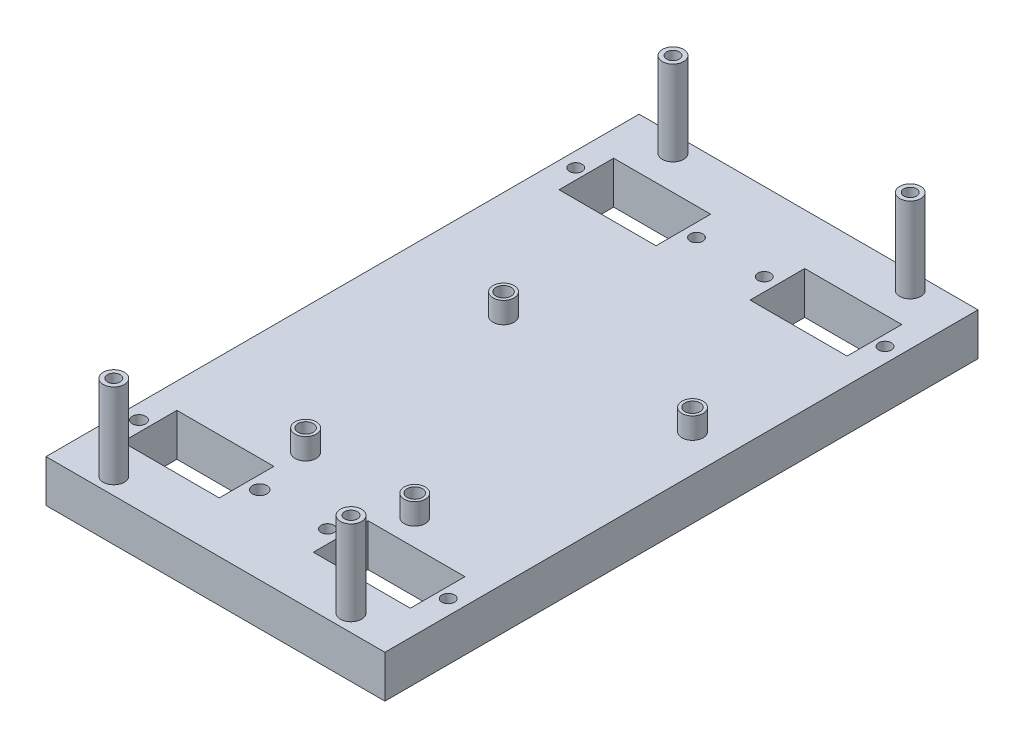
SolidWorks part; units mm, degrees
material "ABS PC"
ref_plane "Front Plane" through (0, 0, 0) normal (0, 0, 1) x (1, 0, 0)
ref_plane "Top Plane" through (0, 0, 0) normal (0, 1, 0) x (1, 0, 0)
ref_plane "Right Plane" through (0, 0, 0) normal (1, 0, 0) x (0, 0, -1)
sketch "Sketch1" plane through (0, 0, 0) normal (0, 1, 0) x (1, 0, 0)
  line L1 (0, 0) -> (-80, 0)
  line L2 (0, 0) -> (0, 140)
  line L3 (0, 140) -> (-80, 140)
  line L4 (-80, 0) -> (-80, 140)
  dimension "D1" = 140
  dimension "D2" = 80
extrude "Boss-Extrude1" add sketch "Sketch1" along normal blind 10
sketch "Sketch4" plane through (0, 10, 0) normal (0, 1, 0) x (1, 0, 0)
  line L0 (0, 140) -> (-80, 140) construction
  line L1 (-6, 128) -> (-28.9, 128)
  line L2 (-6, 128) -> (-6, 115.1)
  line L3 (-6, 115.1) -> (-28.9, 115.1)
  line L4 (-28.9, 128) -> (-28.9, 115.1)
  line L5 (0, 0) -> (0, 140) construction
  dimension "D1" = 12
  dimension "D2" = 12.9
  dimension "D3" = 22.9
  dimension "D4" = 6
extrude "Cut-Extrude2" cut sketch "Sketch4" against normal through all
sketch "Sketch6" plane through (0, 10, 0) normal (0, 1, 0) x (1, 0, 0)
  line L0 (-6, 115.1) -> (-6, 128) construction
  line L1 (0, 140) -> (-80, 140) construction
  circle A0 centre (-3.5, 121.55) radius 1.5
  circle A1 centre (-32, 121.55) radius 1.5
  dimension "D2" = 3
  dimension "D5" = 3
  dimension "D1" = 28.5
  dimension "D3" = 18.45
  dimension "D4" = 18.45
  dimension "D6" = 2.5
extrude "Cut-Extrude4" cut sketch "Sketch6" against normal through all
ref_plane "Plane18" through (0, 0, -70) normal (0, 0, 1) x (1, 0, 0)
mirror "Mirror4" about plane through (0, 0, -70) normal (0, 0, 1) of "Cut-Extrude2", "Cut-Extrude4"
ref_plane "Plane19" through (-40, 0, 0) normal (-1, 0, 0) x (0, 0, 1)
mirror "Mirror15" about plane through (-40, 0, 0) normal (-1, 0, 0) of "Cut-Extrude4", "Cut-Extrude2"
sketch "Sketch9" plane through (0, 10, 0) normal (0, 1, 0) x (1, 0, 0)
  line L1 (-51.1, 24.9) -> (-74, 24.9)
  line L2 (-51.1, 24.9) -> (-51.1, 12)
  line L3 (-51.1, 12) -> (-74, 12)
  line L4 (-74, 24.9) -> (-74, 12)
  line L6 (-80, 140) -> (-80, 0) construction
  line L7 (-80, 0) -> (0, 0) construction
  dimension "D1" = 12.9
  dimension "D2" = 22.9
  dimension "D3" = 6
  dimension "D4" = 12
extrude "Cut-Extrude5" cut sketch "Sketch9" against normal through all
sketch "Sketch13" plane through (0, 10, 0) normal (0, 1, 0) x (1, 0, 0)
  line L0 (0, 140) -> (-80, 140) construction
  line L1 (-80, 140) -> (-80, 0) construction
  circle A0 centre (-68, 136) radius 2.5
  dimension "D3" = 5
  dimension "D1" = 4
  dimension "D2" = 12
extrude "Boss-Extrude2" add sketch "Sketch13" along normal blind 20
sketch "Sketch14" plane through (0, 30, 0) normal (0, 1, 0) x (1, 0, 0)
  circle A0 centre (-68, 136) radius 1.5
  dimension "D1" = 3
extrude "Cut-Extrude8" cut sketch "Sketch14" against normal blind 5
sketch "Sketch15" plane through (0, 10, 0) normal (0, 1, 0) x (1, 0, 0)
  line L0 (0, 140) -> (-80, 140) construction
  line L1 (0, 0) -> (0, 140) construction
  circle A0 centre (-12, 136) radius 2.5
  dimension "D3" = 5
  dimension "D1" = 4
  dimension "D2" = 12
extrude "Boss-Extrude3" add sketch "Sketch15" along normal blind 20
sketch "Sketch16" plane through (0, 30, 0) normal (0, 1, 0) x (1, 0, 0)
  circle A0 centre (-12, 136) radius 1.5
  dimension "D1" = 3
extrude "Cut-Extrude9" cut sketch "Sketch16" against normal blind 5
mirror "Mirror22" about plane through (0, 0, -70) normal (0, 0, 1) of "Cut-Extrude9", "Boss-Extrude3", "Cut-Extrude8", "Boss-Extrude2"
sketch "Sketch17" plane through (0, 10, 0) normal (0, 1, 0) x (1, 0, 0)
  line L2 (-74, 24.9) -> (-74, 12) construction
  line L3 (-80, 0) -> (0, 0) construction
  circle A0 centre (-76.5, 18.45) radius 1.5673
  circle A1 centre (-48, 18.45) radius 1.7104
  dimension "D2" = 2.5
  dimension "D3" = 18.45
  dimension "D4" = 18.45
  dimension "D1" = 28.5
extrude "Cut-Extrude10" cut sketch "Sketch17" against normal through all
sketch "Sketch24" plane through (0, 10, 0) normal (0, 1, 0) x (1, 0, 0)
  circle A0 centre (-54.7039, 82.7047) radius 2.5
  circle A1 centre (-8.7764, 81.3875) radius 2.5
  circle A2 centre (-24.0253, 31.0677) radius 2.5
  circle A3 centre (-50.2143, 31.5023) radius 2.5
  dimension "D1" = 5
  dimension "D2" = 5
  dimension "D3" = 5
  dimension "D4" = 5
extrude "Boss-Extrude5" add sketch "Sketch24" along normal blind 5
sketch "Sketch26" plane through (0, 15, 0) normal (0, 1, 0) x (1, 0, 0)
  circle A0 centre (-54.7039, 82.7047) radius 1.8
  circle A1 centre (-8.7764, 81.3875) radius 1.8
  circle A2 centre (-24.0253, 31.0677) radius 1.8
  circle A3 centre (-50.2143, 31.5023) radius 1.8
  dimension "D1" = 3.6
  dimension "D2" = 3.6
  dimension "D3" = 3.6
  dimension "D4" = 3.6
extrude "Cut-Extrude11" cut sketch "Sketch26" against normal blind 5
